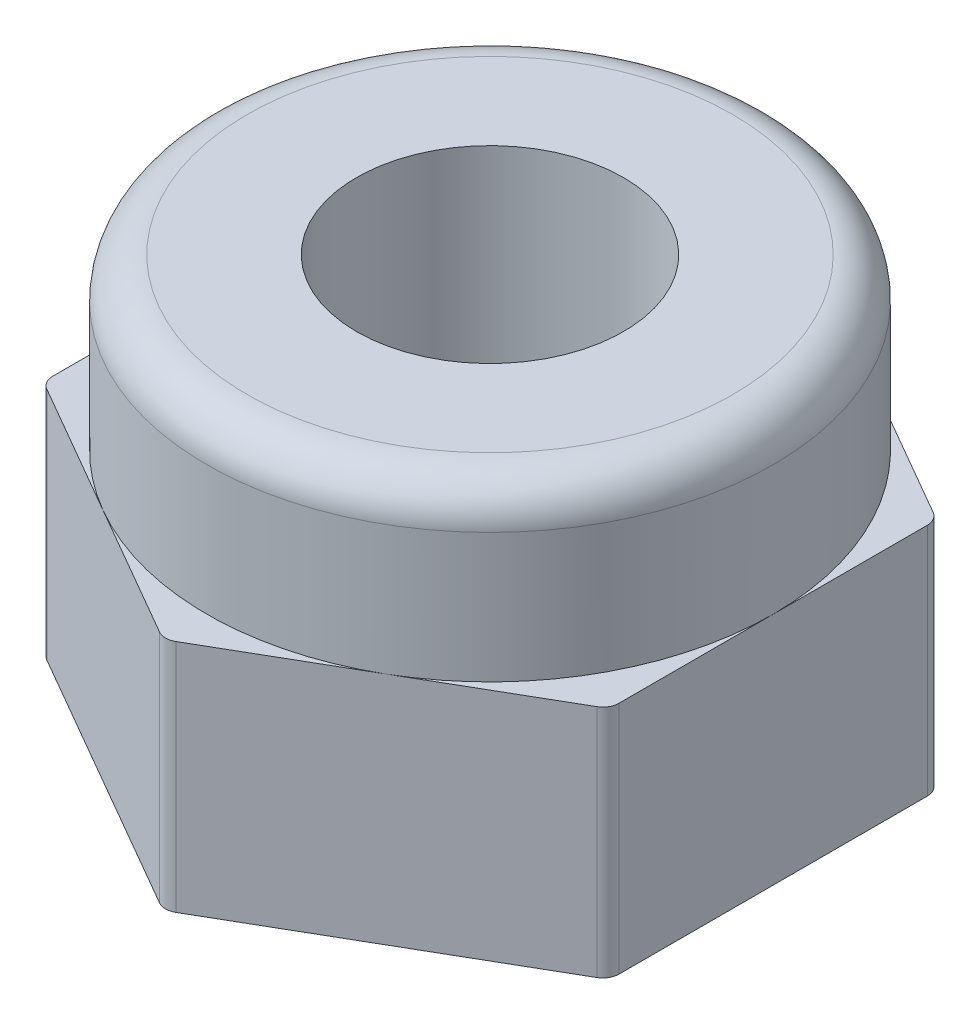
SolidWorks part; units mm, degrees
ref_plane "前视基准面" through (0, 0, 0) normal (0, 0, 1) x (1, 0, 0)
ref_plane "上视基准面" through (0, 0, 0) normal (0, 1, 0) x (1, 0, 0)
ref_plane "右视基准面" through (0, 0, 0) normal (1, 0, 0) x (0, 0, -1)
sketch "草图1" plane through (0, 0, 0) normal (0, 1, 0) x (1, 0, 0)
  line L1 (0, 4.0415) -> (-3.5, 2.0207)
  line L2 (-3.5, 2.0207) -> (-3.5, -2.0207)
  line L3 (-3.5, -2.0207) -> (0, -4.0415)
  line L4 (0, -4.0415) -> (3.5, -2.0207)
  line L5 (3.5, -2.0207) -> (3.5, 2.0207)
  line L6 (3.5, 2.0207) -> (0, 4.0415)
  circle A0 centre (0, 0) radius 3.5 construction
  dimension "D1" = 7
extrude "凸台-拉伸1" add sketch "草图1" along normal blind 2.9
sketch "草图2" plane through (0, 0, 0) normal (0, -1, 0) x (1, 0, 0)
  line L0 (3.5, 2.0207) -> (3.5, -2.0207) construction
  circle A0 centre (0, 0) radius 3.5
extrude "凸台-拉伸2" add sketch "草图2" against normal blind 5
fillet "圆角1" radius 0.5 1 edges at (0, 5, -3.5)
fillet "圆角2" radius 0.2 6 edges at (3.5, 1.45, -2.0207) (3.5, 1.45, 2.0207) (0, 1.45, 4.0415) (0, 1.45, -4.0415) (-3.5, 1.45, -2.0207) (-3.5, 1.45, 2.0207)
hole_wizard "M4 螺纹孔1" positions "草图3" profile "草图5" tap size "M4" standard "GB" end condition through all
sketch "草图3" plane through (0, 0, 0) normal (0, -1, 0) x (-1, 0, 0)
  point P0 (0, 0)
sketch "草图5" plane through (0, 0, 0) normal (1, 0, 0) x (0, 0, -1)
  line L0 (0, 0) -> (0, 5)
  line L1 (0, 5) -> (1.65, 5)
  line L2 (1.65, 5) -> (1.65, 0)
  line L5 (1.65, 0) -> (0, 0)
  line L11 (0, -6.35) -> (0, 107.95) construction
  dimension "通孔螺纹孔钻头直径" = 3.3
  dimension "通孔螺纹孔钻头深度" = 5
cosmetic thread "孔螺蚊线1" parameters "D2"=4
